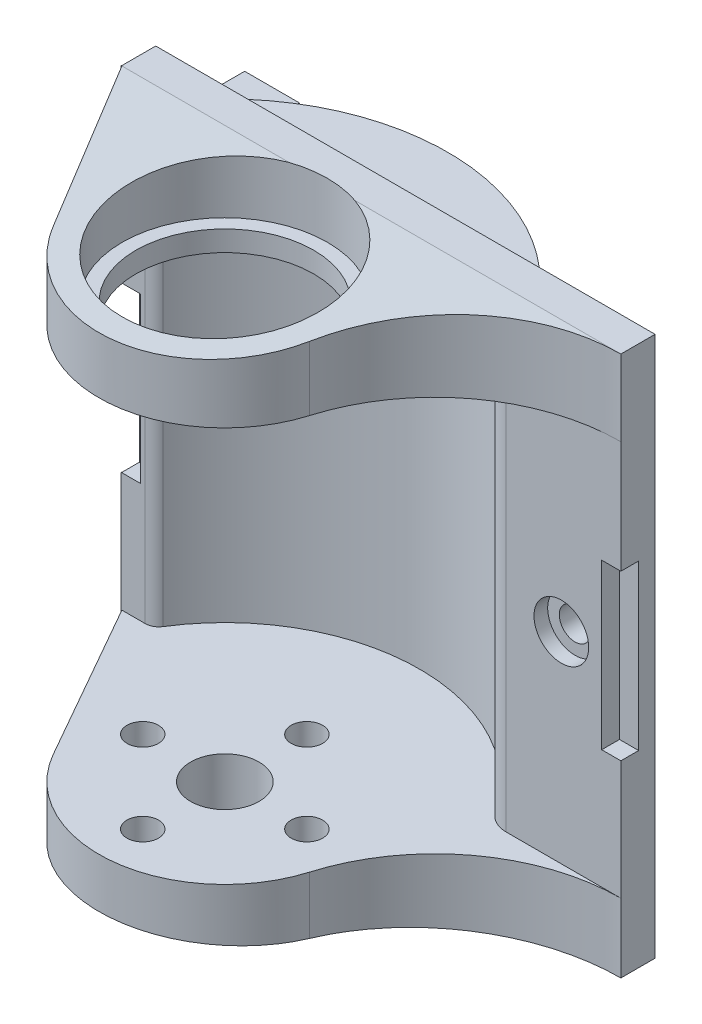
SolidWorks part; units mm, degrees
ref_plane "前视基准面" through (0, 0, 0) normal (0, 0, 1) x (1, 0, 0)
ref_plane "上视基准面" through (0, 0, 0) normal (0, 1, 0) x (1, 0, 0)
ref_plane "右视基准面" through (0, 0, 0) normal (1, 0, 0) x (0, 0, -1)
sketch "草图1" plane through (0, 0, 0) normal (0, 1, 0) x (1, 0, 0)
  circle A1 centre (0, 0) radius 16.3
  dimension "D1" = 32.6
extrude "凸台-拉伸1" add sketch "草图1" along normal mid plane 39.5
sketch "草图2" plane through (0, -19.75, 0) normal (0, -1, 0) x (1, 0, 0)
  line L1 (-14.65, -7.1) -> (21.85, -7.1)
  line L2 (-14.65, -7.1) -> (-14.65, -9.6)
  line L3 (-14.65, -9.6) -> (21.85, -9.6)
  line L4 (21.85, -7.1) -> (21.85, -9.6)
  dimension "D1" = 2.5
  dimension "D2" = 9.6
  dimension "D3" = 36.5
  dimension "D4" = 14.65
extrude "凸台-拉伸2" add sketch "草图2" against normal through all
sketch "草图3" plane through (0, -19.75, 0) normal (0, -1, 0) x (1, 0, 0)
  line L1 (21.85, -7.1) -> (-22.9944, -7.1)
  line L2 (21.85, -7.1) -> (21.85, 18.4067)
  line L3 (21.85, 18.4067) -> (-22.9944, 18.4067)
  line L4 (-22.9944, -7.1) -> (-22.9944, 18.4067)
extrude "切除-拉伸1" cut sketch "草图3" against normal blind 50
sketch "草图4" plane through (0, -19.75, 0) normal (0, -1, 0) x (1, 0, 0)
  line L0 (-14.65, -7.1462) -> (-7.9965, 4.5492)
  line L1 (21.85, -7.1) -> (21.85, 7.9567) construction
  line L2 (-14.65, -7.1462) -> (21.85, -7.1)
  arc A0 (8.8187, 2.6213) -> (-7.9965, 4.5492) centre (0, 0) ccw
  arc A1 (8.8187, 2.6213) -> (21.85, -7.1) centre (21.85, 6.4949) ccw
  dimension "D1" = 18.4
extrude "凸台-拉伸3" add sketch "草图4" against normal blind 5.05
mirror "镜向1" about plane through (0, 0, 0) normal (0, 1, 0) of "凸台-拉伸3"
sketch "草图5" plane through (0, -14.7, 0) normal (0, 1, 0) x (1, 0, 0)
  circle A0 centre (0, 0) radius 14.25
  dimension "D1" = 28.5
extrude "切除-拉伸2" cut sketch "草图5" along normal up to surface (29.4 mm away) up to face at (1.768, 14.7, -0.9093)
sketch "草图6" plane through (0, -14.7, 0) normal (0, 1, 0) x (1, 0, 0)
  circle A0 centre (0, 0) radius 2.5
  dimension "D1" = 5
extrude "切除-拉伸3" cut sketch "草图6" against normal through all
sketch "草图9" plane through (0, 19.75, 0) normal (0, 1, 0) x (1, 0, 0)
  circle A0 centre (0, 0) radius 7.5
  dimension "D1" = 15
extrude "切除-拉伸6" cut sketch "草图9" against normal up to next
sketch "草图12" plane through (0, 0, -7.1) normal (0, 0, 1) x (1, 0, 0)
  line L0 (0, 0) -> (30.0134, 0) construction
  line L1 (21.85, 14.7) -> (21.85, -14.7) construction
  circle A0 centre (17.5, 0) radius 1.15
  dimension "D1" = 2.3
  dimension "D2" = 4.35
extrude "切除-拉伸9" cut sketch "草图12" against normal through all
sketch "草图13" plane through (0, 0, -7.1) normal (0, 0, 1) x (1, 0, 0)
  circle A0 centre (17.5, 0) radius 2
  dimension "D1" = 4
extrude "切除-拉伸10" cut sketch "草图13" against normal blind 1
sketch "草图14" plane through (0, 0, -7.1) normal (0, 0, 1) x (1, 0, 0)
  line L0 (21.85, 14.7) -> (21.85, -14.7) construction
  line L1 (20.45, -6) -> (23.25, -6)
  line L2 (20.45, -6) -> (20.45, 6)
  line L3 (20.45, 6) -> (23.25, 6)
  line L4 (23.25, -6) -> (23.25, 6)
  line L5 (20.45, -6) -> (23.25, 6) construction
  line L6 (20.45, 6) -> (23.25, -6) construction
  point P0 (21.85, 0)
  dimension "12" = 12
  dimension "D2" = 2.8
extrude "切除-拉伸11" cut sketch "草图14" against normal blind 1.3
sketch "草图15" plane through (0, 0, -7.1) normal (0, 0, 1) x (1, 0, 0)
  line L0 (0, 0) -> (-23.1213, 0) construction
  line L1 (-14.6724, -19.75) -> (-14.6724, 19.75) construction
  line L2 (-16.0724, -6) -> (-13.2724, -6)
  line L3 (-16.0724, -6) -> (-16.0724, 6)
  line L4 (-16.0724, 6) -> (-13.2724, 6)
  line L5 (-13.2724, -6) -> (-13.2724, 6)
  line L6 (-16.0724, -6) -> (-13.2724, 6) construction
  line L7 (-16.0724, 6) -> (-13.2724, -6) construction
  point P3 (-14.6724, 0)
  dimension "D1" = 12
  dimension "D2" = 2.8
extrude "切除-拉伸12" cut sketch "草图15" against normal blind 1.3
ref_plane "基准面1" through (0, 0, -15.1) normal (0, 0, -1) x (-1, 0, 0)
sketch "草图16" plane through (0, 0, -15.1) normal (0, 0, -1) x (-1, 0, 0)
  line L0 (14.65, 19.75) -> (14.65, -19.75) construction
  line L1 (9.65, 10.9) -> (13.65, 10.9)
  line L2 (9.65, 10.9) -> (9.65, 15.9)
  line L3 (9.65, 15.9) -> (13.65, 15.9)
  line L4 (13.65, 10.9) -> (13.65, 15.9)
  line L5 (9.65, 10.9) -> (13.65, 15.9) construction
  line L6 (9.65, 15.9) -> (13.65, 10.9) construction
  line L7 (0, 0) -> (27.535, 0) construction
  point P0 (11.65, 13.4)
  dimension "D1" = 1
  dimension "D2" = 10.9
  dimension "D3" = 5
  dimension "D4" = 4
extrude "凸台-拉伸5" add sketch "草图16" against normal up to surface (1.9635 mm away)
mirror "镜向4" about plane through (0, 0, 0) normal (0, 1, 0) of "凸台-拉伸5"
sketch "草图17" plane through (0, 0, -15.1) normal (0, 0, -1) x (-1, 0, 0)
  line L0 (11.65, 15.9) -> (11.65, 12.48) construction
  line L1 (13.65, 15.9) -> (9.65, 15.9) construction
  line L2 (13.65, 13.4) -> (11.1035, 13.4) construction
  line L3 (13.65, 10.9) -> (13.65, 15.9) construction
  line L5 (11.15, 12.4) -> (12.15, 12.4)
  line L6 (11.15, 12.4) -> (11.15, 14.4)
  line L7 (11.15, 14.4) -> (12.15, 14.4)
  line L8 (12.15, 12.4) -> (12.15, 14.4)
  line L9 (11.15, 12.4) -> (12.15, 14.4) construction
  line L10 (11.15, 14.4) -> (12.15, 12.4) construction
  point P8 (11.65, 13.4)
  dimension "D1" = 2
  dimension "D2" = 1
extrude "切除-拉伸13" cut sketch "草图17" against normal blind 2.5
mirror "镜向5" about plane through (0, 0, 0) normal (0, 1, 0) of "切除-拉伸13"
sketch "草图19" plane through (0, 19.75, 0) normal (0, 1, 0) x (1, 0, 0)
  circle A1 centre (0, 0) radius 6.5
  circle A2 centre (0, 0) radius 8.519
  dimension "D1" = 13
extrude "凸台-拉伸6" add sketch "草图19" against normal blind 2.25
sketch "草图20" plane through (0, -19.75, 0) normal (0, -1, 0) x (1, 0, 0)
  circle A0 centre (0, 6) radius 1.15
  dimension "D1" = 2.3
  dimension "D2" = 6
extrude "切除-拉伸18" cut sketch "草图20" against normal up to next
pattern_circular "阵列(圆周)1" count 4 over 360 about axis through (0, 0, 0) along (0, 1, 0) of "切除-拉伸18"
sketch "草图7" plane through (-14.65, 0, 0) normal (-1, 0, 0) x (0, 0, 1)
  line L0 (-7.1, 19.75) -> (9.2, 18.3239)
  line L1 (9.2, 14.7) -> (9.2, 19.75) construction
  line L2 (9.2, 18.3239) -> (9.2, 19.75)
  line L3 (9.2, 19.75) -> (-7.1, 19.75)
  dimension "D1" = 5
extrude "切除-拉伸8" cut sketch "草图7" against normal through all
mirror "镜向3" about plane through (0, 0, 0) normal (0, 1, 0) of "切除-拉伸8"
sketch "草图18" plane through (0, 0, -9.6) normal (0, 0, -1) x (-1, 0, 0)
  line L0 (-13.1731, 19.75) -> (-13.1731, -19.75) construction
  line L1 (13.1731, 19.75) -> (-13.1731, 19.75)
  line L2 (13.1731, 19.75) -> (13.1731, 17)
  line L3 (13.1731, 17) -> (-13.1731, 17)
  line L4 (-13.1731, 19.75) -> (-13.1731, 17)
  dimension "D1" = 2.75
extrude "切除-拉伸16" cut sketch "草图18" along normal blind 12.5
mirror "镜向6" about plane through (0, 0, 0) normal (0, 1, 0) of "切除-拉伸16"
fillet "圆角1" radius 2 1 edges at (12.3553, 0, -7.1)
fillet "圆角2" radius 1 1 edges at (-12.3553, 0, -7.1)
sketch "草图21" plane through (0, -19.75, 0) normal (0, -1, 0) x (1, 0, 0)
  circle A0 centre (0, 6) radius 2.1
  circle A1 centre (-6, 0) radius 2.1
  circle A2 centre (6, 0) radius 2.1
  circle A3 centre (0, -6) radius 2.1
  dimension "D1" = 4.2
extrude "切除-拉伸19" cut sketch "草图21" against normal blind 2.5
sketch "草图22" plane through (0, 17.5, 0) normal (0, -1, 0) x (1, 0, 0)
  circle A0 centre (0, 0) radius 7.5
  dimension "D1" = 15
extrude "切除-拉伸23" cut sketch "草图22" against normal blind 10
sketch "草图23" plane through (0, 14.7, 0) normal (0, -1, 0) x (1, 0, 0)
  circle A0 centre (0, 0) radius 6.5
  circle A2 centre (0, 0) radius 7.5
  dimension "D1" = 13
  dimension "D2" = 15
extrude "凸台-拉伸7" add sketch "草图23" against normal blind 1
other "移动面3" face at (0.8982, 14.7, -4.943) parameters "D1"=0.5
